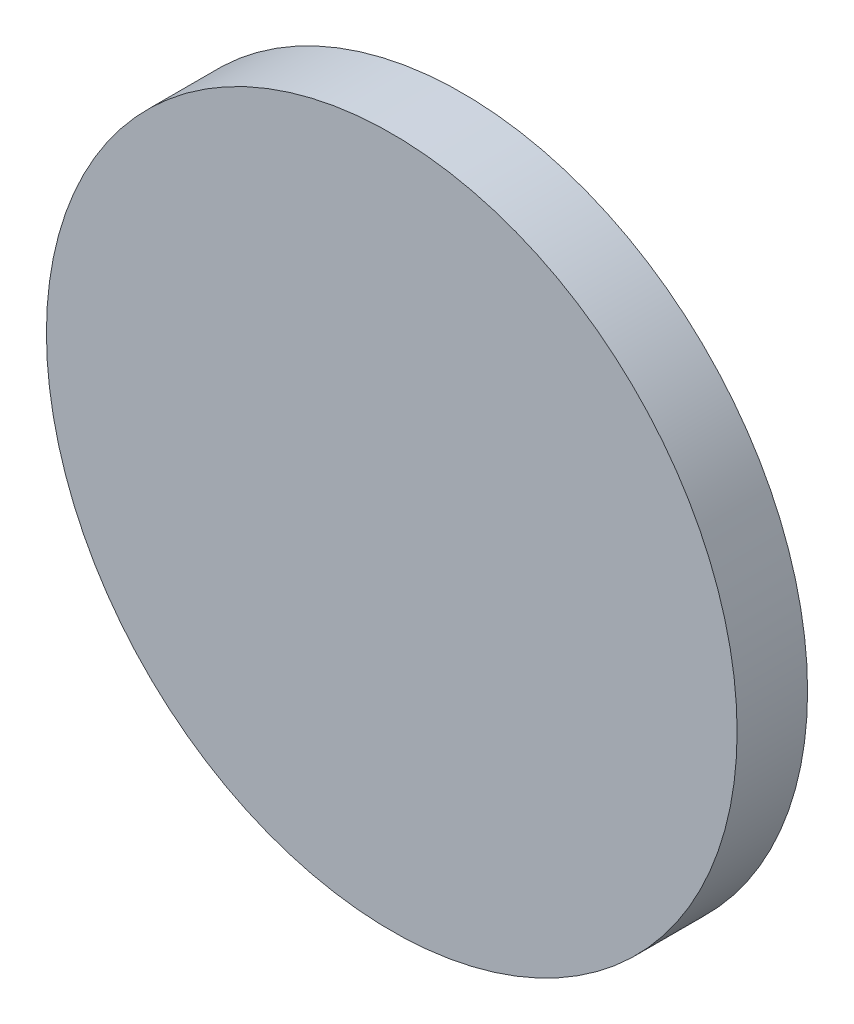
SolidWorks part; units mm, degrees
ref_plane "前视基准面" through (0, 0, 0) normal (0, 0, 1) x (1, 0, 0)
ref_plane "上视基准面" through (0, 0, 0) normal (0, 1, 0) x (1, 0, 0)
ref_plane "右视基准面" through (0, 0, 0) normal (1, 0, 0) x (0, 0, -1)
other "Configuration Table"
sketch "草图1" plane through (0, 0, 0) normal (0, 1, 0) x (1, 0, 0)
  line L0 (0, -2.04) -> (0, 1.6572) construction
  line L1 (10, 0) -> (10, -2.04)
  line L2 (10, -2.04) -> (0, -2.04)
  line L3 (0, 1.6572) -> (0, -2.04)
  line L4 (10, 0) -> (0, 0) construction
  arc A0 (0, 1.6572) -> (10, 0) centre (0, -29.3428) cw
  point P5 (0, 0)
  dimension "D1" = 31
  dimension "D2" = 2.04
  dimension "D3" = 10
revolve "旋转1" add sketch "草图1" angle 360 about L0
